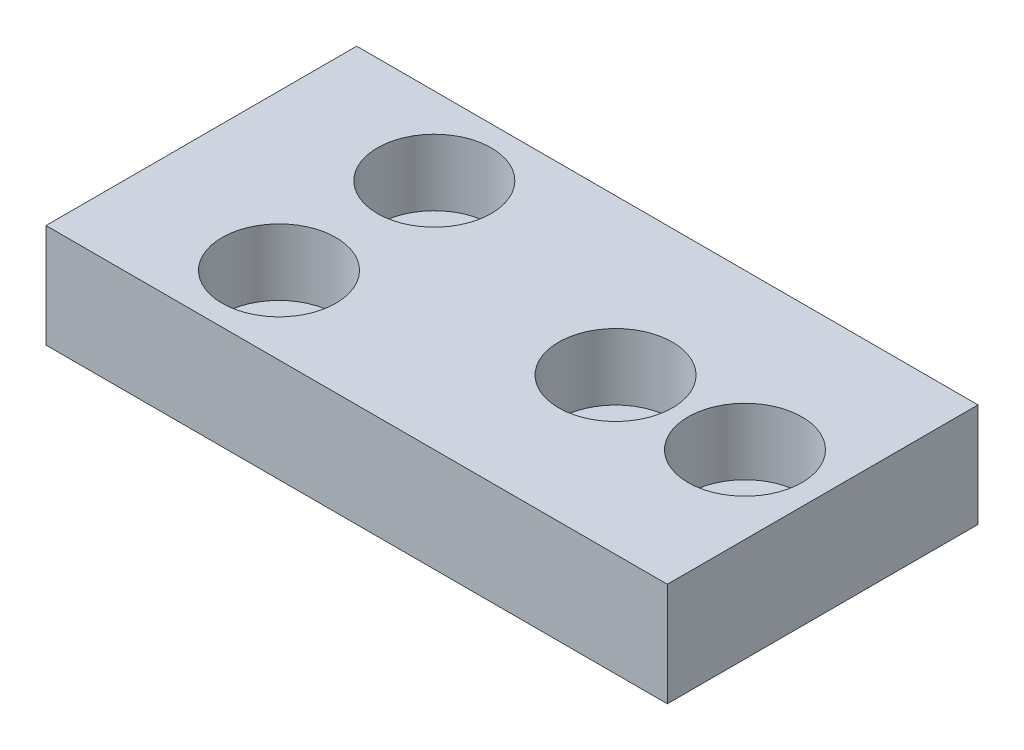
SolidWorks part; units mm, degrees
ref_plane "Front Plane" through (0, 0, 0) normal (0, 0, 1) x (1, 0, 0)
ref_plane "Top Plane" through (0, 0, 0) normal (0, 1, 0) x (1, 0, 0)
ref_plane "Right Plane" through (0, 0, 0) normal (1, 0, 0) x (0, 0, -1)
sketch "Sketch1" plane through (0, 0, 0) normal (0, 1, 0) x (1, 0, 0)
  line L1 (-30, 15) -> (30, 15)
  line L2 (-30, 15) -> (-30, -15)
  line L3 (-30, -15) -> (30, -15)
  line L4 (30, 15) -> (30, -15)
  line L5 (-30, 15) -> (30, -15) construction
  line L6 (-30, -15) -> (30, 15) construction
  point P0 (0, 0)
  dimension "D1" = 60
  dimension "D2" = 30
extrude "Boss-Extrude1" add sketch "Sketch1" along normal mid plane 10
hole_wizard "CBORE for M6 Hex Socket Head Cap Screw1" positions "Sketch4" profile "Sketch3" counterbore size "M6" standard "ISO" end condition through all
sketch "Sketch4" plane through (0, 5, 0) normal (0, 1, 0) x (1, 0, 0)
  line L0 (-30, 15) -> (-30, -15) construction
  point P0 (-15, 7.5)
  point P2 (-15, -7.5)
  dimension "D1" = 15
  dimension "D2" = 15
  dimension "D3" = 7.5
sketch "Sketch3" plane through (-15, 5, -7.5) normal (1, 0, 0) x (0, 0, 1)
  line L0 (0, 0) -> (0, 10)
  line L1 (0, 10) -> (3.3, 10)
  line L3 (3.3, 10) -> (3.3, 6.4)
  line L4 (3.3, 6.4) -> (5.5, 6.4)
  line L5 (5.5, 6.4) -> (5.5, 0)
  line L7 (5.5, 0) -> (0, 0)
  line L11 (0, -6.35) -> (0, 107.95) construction
  dimension "Thru Hole Dia." = 6.6
  dimension "Thru Hole Depth" = 10
  dimension "C'Bore Dia." = 11
  dimension "C'Bore Depth" = 6.4
hole_wizard "CBORE for M6 Hex Socket Head Cap Screw2" positions "Sketch5" profile "Sketch6" counterbore size "M6" standard "ISO" end condition through all
sketch "Sketch5" plane through (0, 5, 0) normal (0, 1, 0) x (1, 0, 0)
  circle A0 centre (-15, -7.5) radius 3.3 construction
  point P0 (10, 0)
  point P2 (22.5, 0)
  point P7 (0, 0)
  point P8 (0, 0)
  dimension "D1" = 25
  dimension "D2" = 12.5
sketch "Sketch6" plane through (10, 5, 0) normal (1, 0, 0) x (0, 0, 1)
  line L0 (0, 0) -> (0, 10)
  line L1 (0, 10) -> (3.3, 10)
  line L3 (3.3, 10) -> (3.3, 6.4)
  line L4 (3.3, 6.4) -> (5.5, 6.4)
  line L5 (5.5, 6.4) -> (5.5, 0)
  line L7 (5.5, 0) -> (0, 0)
  line L11 (0, -6.35) -> (0, 107.95) construction
  dimension "Thru Hole Dia." = 6.6
  dimension "Thru Hole Depth" = 10
  dimension "C'Bore Dia." = 11
  dimension "C'Bore Depth" = 6.4
